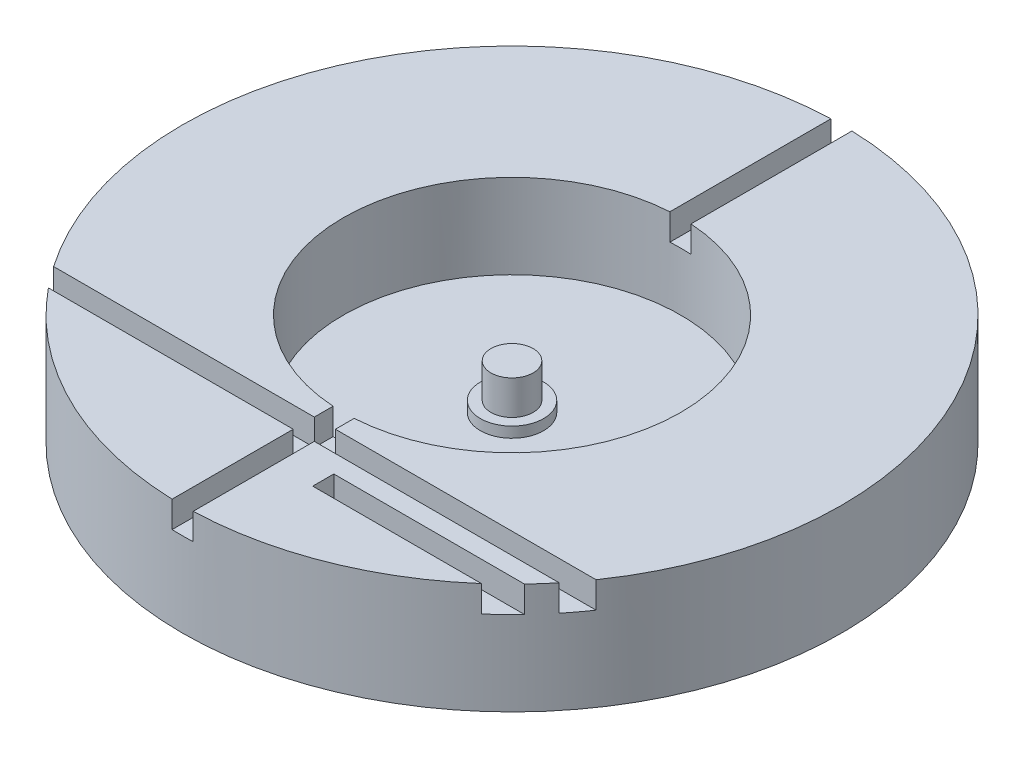
SolidWorks part; units mm, degrees
material "Cast Alloy Steel"
ref_plane "Front Plane" through (0, 0, 0) normal (0, 0, 1) x (1, 0, 0)
ref_plane "Top Plane" through (0, 0, 0) normal (0, 1, 0) x (1, 0, 0)
ref_plane "Right Plane" through (0, 0, 0) normal (1, 0, 0) x (0, 0, -1)
sketch "Sketch1" plane through (0, 0, 0) normal (0, 1, 0) x (1, 0, 0)
  circle A0 centre (0, 0) radius 62.5
  dimension "D1" = 125
extrude "Boss-Extrude1" add sketch "Sketch1" along normal blind 21
sketch "Sketch2" plane through (0, 21, 0) normal (0, 1, 0) x (1, 0, 0)
  circle A0 centre (0, 0) radius 32
  circle A1 centre (0, 0) radius 6
  dimension "D1" = 64
extrude "Cut-Extrude1" cut sketch "Sketch2" against normal blind 16
sketch "Sketch3" plane through (0, 21, 0) normal (0, 1, 0) x (1, 0, 0)
  circle A0 centre (0, 0) radius 6
  circle A1 centre (0, 0) radius 4
extrude "Cut-Extrude2" cut sketch "Sketch3" against normal blind 14
sketch "Sketch4" plane through (0, 21, 0) normal (0, 1, 0) x (1, 0, 0)
  circle A0 centre (0, 0) radius 4
extrude "Cut-Extrude3" cut sketch "Sketch4" against normal blind 7.5
sketch "Sketch5" plane through (0, 21, 0) normal (0, 1, 0) x (1, 0, 0)
  line L0 (0, 0) -> (2, 0) construction
  line L1 (0, 0) -> (-2, 0) construction
  line L2 (2, 62.468) -> (2, -62.468)
  line L3 (-2, 62.468) -> (-2, -62.468)
  circle A0 centre (0, 0) radius 62.5 construction
  arc A1 (-2, -62.468) -> (2, -62.468) centre (0, 0) ccw
  arc A2 (2, 62.468) -> (-2, 62.468) centre (0, 0) ccw
  dimension "D1" = 2
  dimension "D2" = 2
extrude "Cut-Extrude4" cut sketch "Sketch5" against normal blind 5
sketch "Sketch6" plane through (0, 21, 0) normal (0, 1, 0) x (1, 0, 0)
  line L0 (0, 0) -> (0, -37.5) construction
  line L2 (-48.4355, -39.5) -> (48.4355, -39.5)
  line L4 (-51.4393, -35.5) -> (51.4393, -35.5)
  line L6 (-48.5276, -39.3868) -> (51.4393, -35.5) construction
  line L7 (-51.4393, -35.5) -> (48.5276, -39.3868) construction
  arc A0 (2, -62.468) -> (2, 62.468) centre (0, 0) ccw construction
  arc A1 (-51.4393, -35.5) -> (-48.4355, -39.5) centre (0, 0) ccw
  arc A2 (48.4355, -39.5) -> (51.4393, -35.5) centre (0, 0) ccw
  dimension "D1" = 37.5
  dimension "D2" = 96.871
  dimension "D3" = 102.8786
extrude "Cut-Extrude5" cut sketch "Sketch6" against normal blind 5
sketch "Sketch9" plane through (0, 21, 0) normal (0, 1, 0) x (1, 0, 0)
  line L0 (0, 0) -> (0, -45) construction
  line L1 (0, -45) -> (43.3734, -45) construction
  line L2 (41.1977, -43) -> (45.3569, -43)
  line L3 (9.1977, -43) -> (41.1977, -43)
  line L4 (9.1977, -43) -> (9.1977, -47)
  line L5 (9.1977, -47) -> (41.1977, -47)
  line L6 (41.1977, -45) -> (41.1977, -47)
  line L7 (9.1977, -43) -> (41.1977, -47) construction
  line L8 (9.1977, -47) -> (41.1977, -43) construction
  arc A0 (41.1977, -47) -> (45.3569, -43) centre (0, 0) ccw
  arc A1 (2, -62.468) -> (48.4355, -39.5) centre (0, 0) ccw construction
  point P3 (25.1977, -45)
  dimension "D1" = 45
  dimension "D2" = 32
  dimension "D3" = 4
  dimension "D4" = 25.1977
extrude "Cut-Extrude6" cut sketch "Sketch9" against normal blind 5
